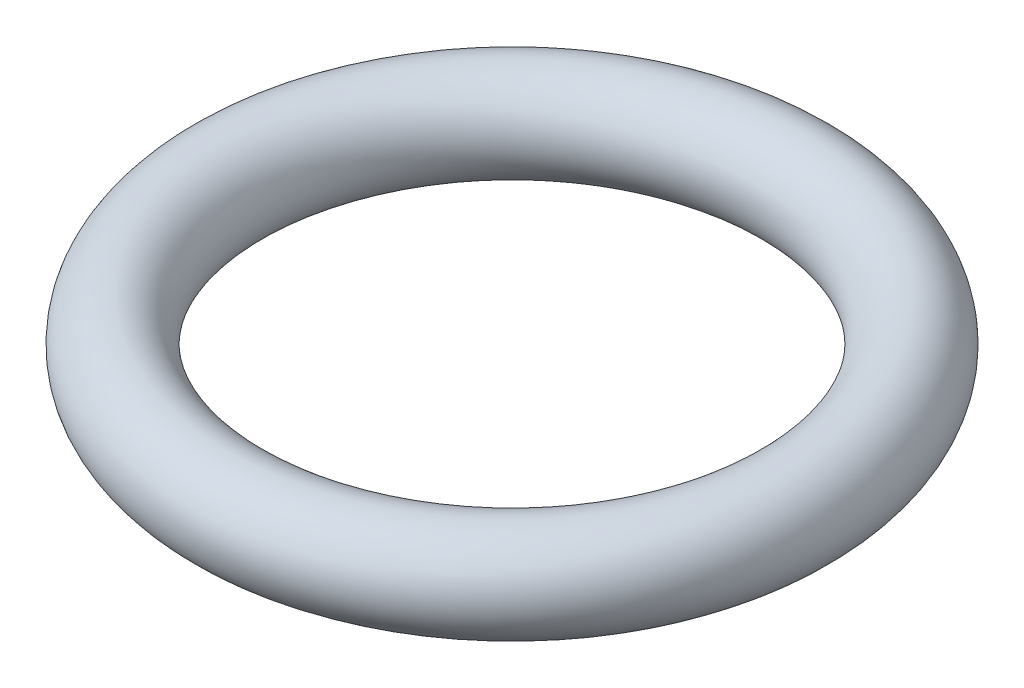
SolidWorks part; units mm, degrees
ref_plane "Front Plane" through (0, 0, 0) normal (0, 0, 1) x (1, 0, 0)
ref_plane "Top Plane" through (0, 0, 0) normal (0, 1, 0) x (1, 0, 0)
ref_plane "Right Plane" through (0, 0, 0) normal (1, 0, 0) x (0, 0, -1)
sketch "Sketch1" plane through (0, 0, 0) normal (0, 0, 1) x (1, 0, 0)
  line L0 (0, 0) -> (64.1898, 0) construction
  line L1 (0, 0) -> (0, 55.4832) construction
  circle A0 centre (152.4, 0) radius 25.4
  point P5 (177.8, 0)
  dimension "D2" = 50.8
  dimension "D1" = 177.8
revolve "Revolve1" add sketch "Sketch1" angle 360 about L1
sketch "Sketch3" plane through (0, 0, 0) normal (0, 1, 0) x (1, 0, 0)
  circle A0 centre (0, 0) radius 237.3374
extrude "Cut-Extrude1" cut sketch "Sketch3" against normal through all from offset 24.13
